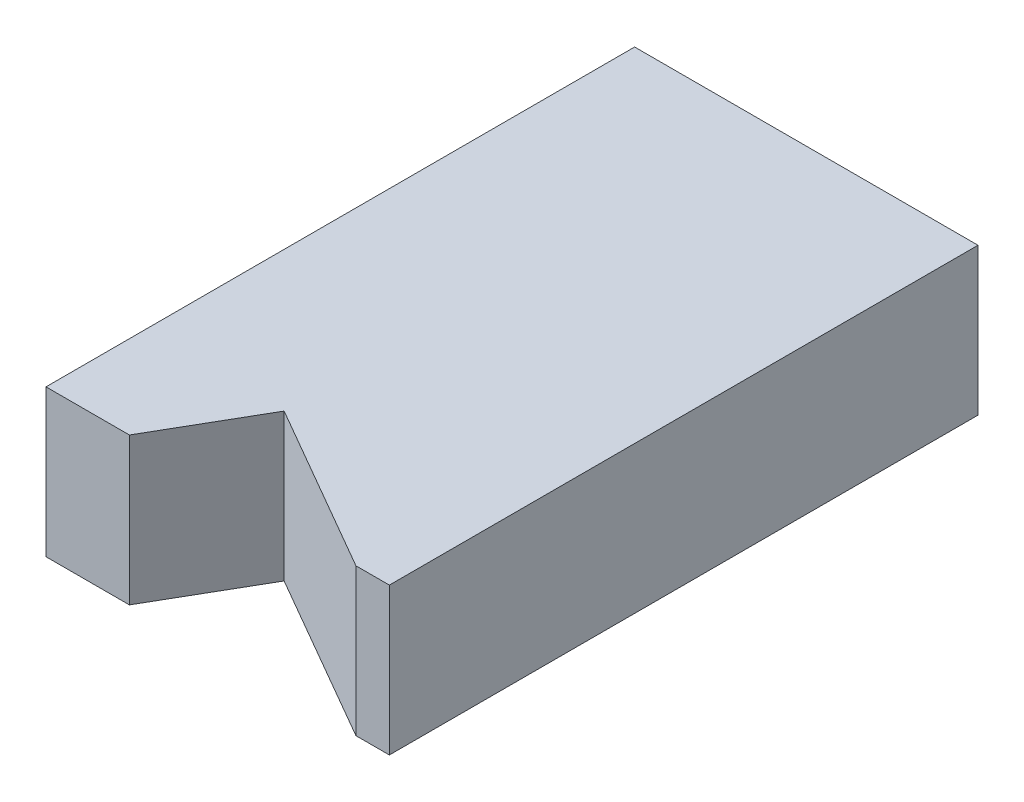
SolidWorks part; units mm, degrees
material "Pine"
ref_plane "X-Y Datum" through (0, 0, 0) normal (0, 0, 1) x (1, 0, 0)
ref_plane "X-Z Datum" through (0, 0, 0) normal (0, 1, 0) x (1, 0, 0)
ref_plane "Y-Z Datum" through (0, 0, 0) normal (1, 0, 0) x (0, 0, -1)
sketch "Sketch2" plane through (0, 0, 0) normal (0, 0, 1) x (1, 0, 0)
  line L1 (0, 0) -> (101.6, 0)
  line L2 (0, 0) -> (0, 50.8)
  line L3 (0, 50.8) -> (101.6, 50.8)
  line L4 (101.6, 0) -> (101.6, 50.8)
  dimension "D1" = 101.6
  dimension "D2" = 50.8
extrude "Boss-Extrude1" add sketch "Sketch2" along normal blind 152.4
sketch "Sketch3" plane through (0, 0, 0) normal (0, -1, 0) x (1, 0, 0)
  line L0 (34.29, 152.4) -> (48.9547, 127)
  line L1 (0, 152.4) -> (101.6, 152.4) construction
  line L2 (48.9547, 127) -> (92.9488, 152.4)
  dimension "D1" = 120
  dimension "D2" = 34.29
  dimension "D3" = 50.8
extrude "Cut-Extrude1" cut sketch "Sketch3" against normal through all both and the other way through all
sketch "Sketch4" plane through (0, 0, 152.4) normal (0, 0, 1) x (1, 0, 0)
  line L1 (101.6, 0) -> (12.7, 0)
  line L2 (101.6, 0) -> (101.6, 38.1)
  line L3 (101.6, 38.1) -> (12.7, 38.1)
  line L4 (12.7, 0) -> (12.7, 38.1)
  line L5 (101.6, 0) -> (0, 0)
  line L6 (101.6, 0) -> (101.6, 50.8)
  line L7 (101.6, 50.8) -> (0, 50.8)
  line L8 (0, 0) -> (0, 50.8)
  line M3 (0, 0) -> (34.29, 0)
  line M4 (34.29, 0) -> (34.29, 50.8)
  line M5 (34.29, 50.8) -> (0, 50.8)
  line M6 (0, 50.8) -> (0, 0)
  dimension "D1" = 38.1
  dimension "D2" = 88.9
extrude "Cut-Extrude2" cut sketch "Sketch4" against normal through all both and the other way through all contours L4 L3 M3 M4 M5 M6 | L6 L7 L3 M4
